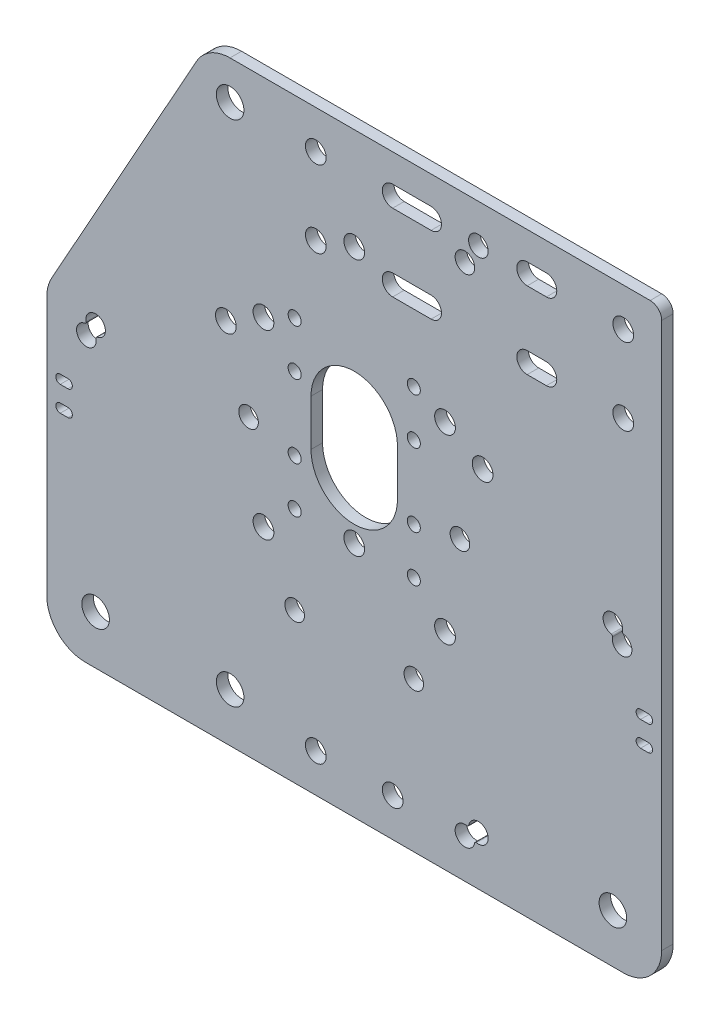
SolidWorks part; units mm, degrees
ref_plane "Ebene vorne" through (0, 0, 0) normal (0, 0, 1) x (1, 0, 0)
ref_plane "Ebene oben" through (0, 0, 0) normal (0, 1, 0) x (1, 0, 0)
ref_plane "Ebene rechts" through (0, 0, 0) normal (1, 0, 0) x (0, 0, -1)
sketch "Model" plane through (0, 0, 0) normal (0, 0, 1) x (1, 0, 0)
  line L0 (157, 155) -> (47.6787, 155)
  line L1 (38.941, 149.8633) -> (1.2623, 82.1679)
  line L2 (0, 77.3045) -> (0, 10)
  line L3 (10, 0) -> (150, 0)
  line L4 (160, 10) -> (160, 152)
  line L5 (68.75, 89.3) -> (68.75, 77.3)
  line L6 (91.25, 77.3) -> (91.25, 89.3)
  line L7 (130, 147.7) -> (125, 147.7)
  line L8 (125, 142.3) -> (130, 142.3)
  line L9 (130, 127.7) -> (125, 127.7)
  line L10 (125, 122.3) -> (130, 122.3)
  line L11 (100, 127.7) -> (90, 127.7)
  line L12 (90, 122.3) -> (100, 122.3)
  line L13 (100, 147.7) -> (90, 147.7)
  line L14 (90, 142.3) -> (100, 142.3)
  line L15 (5.5, 55.15) -> (3.5, 55.15)
  line L16 (3.5, 52.85) -> (5.5, 52.85)
  line L17 (5.5, 61.65) -> (3.5, 61.65)
  line L18 (3.5, 59.35) -> (5.5, 59.35)
  line L19 (156.5, 55.15) -> (154.5, 55.15)
  line L20 (154.5, 52.85) -> (156.5, 52.85)
  line L21 (156.5, 61.65) -> (154.5, 61.65)
  line L22 (154.5, 59.35) -> (156.5, 59.35)
  circle A0 centre (12.7, 12.7) radius 3.59
  circle A1 centre (47.7, 12.7) radius 3.59
  circle A2 centre (147.3, 12.7) radius 3.59
  circle A3 centre (47.7, 145) radius 3.59
  circle A4 centre (112.3, 145) radius 2.55
  circle A5 centre (52.5, 76.5) radius 2.55
  circle A6 centre (107.5, 76.5) radius 2.55
  circle A7 centre (64.5, 39) radius 2.55
  circle A8 centre (95.5, 39) radius 2.55
  circle A9 centre (64.5, 61.8) radius 1.7
  circle A10 centre (64.5, 73.8) radius 1.7
  circle A11 centre (64.5, 92.8) radius 1.7
  circle A12 centre (64.5, 104.8) radius 1.7
  circle A13 centre (95.5, 61.8) radius 1.7
  circle A14 centre (95.5, 73.8) radius 1.7
  circle A15 centre (95.5, 92.8) radius 1.7
  circle A16 centre (95.5, 104.8) radius 1.7
  circle A17 centre (56.38, 53.68) radius 2.7
  circle A18 centre (103.62, 53.68) radius 2.7
  circle A19 centre (103.62, 100.92) radius 2.7
  circle A20 centre (56.38, 100.92) radius 2.7
  circle A21 centre (70, 145) radius 2.7
  circle A22 centre (150, 145) radius 2.7
  circle A23 centre (150, 125) radius 2.7
  circle A24 centre (108.8, 139.5) radius 2.55
  circle A25 centre (80, 61.8) radius 2.7
  circle A26 centre (113.4037, 95.2037) radius 2.7
  circle A27 centre (80, 128.6074) radius 2.7
  circle A28 centre (46.5963, 95.2037) radius 2.7
  circle A29 centre (90, 10) radius 2.7
  circle A30 centre (70, 10) radius 2.7
  circle A31 centre (70, 125) radius 2.7
  arc A32 (47.6787, 155) -> (38.941, 149.8633) centre (47.6787, 145) ccw
  arc A33 (1.2623, 82.1679) -> (0, 77.3045) centre (10, 77.3045) ccw
  arc A34 (0, 10) -> (10, 0) centre (10, 10) ccw
  arc A35 (150, 0) -> (160, 10) centre (150, 10) ccw
  arc A36 (160, 152) -> (157, 155) centre (157, 152) ccw
  arc A37 (109.3109, 12.7983) -> (111.3145, 9.8763) centre (108.8, 10.3) ccw
  arc A38 (111.7891, 10.2017) -> (111.3145, 9.8763) centre (111.709, 9.8098) ccw
  arc A39 (111.7891, 10.2017) -> (109.7855, 13.1237) centre (112.3, 12.7) ccw
  arc A40 (109.3109, 12.7983) -> (109.7855, 13.1237) centre (109.391, 13.1902) ccw
  arc A41 (147.2017, 74.3109) -> (150.1237, 76.3145) centre (149.7, 73.8) ccw
  arc A42 (149.7983, 76.7891) -> (150.1237, 76.3145) centre (150.1902, 76.709) ccw
  arc A43 (149.7983, 76.7891) -> (146.8763, 74.7855) centre (147.3, 77.3) ccw
  arc A44 (147.2017, 74.3109) -> (146.8763, 74.7855) centre (146.8098, 74.391) ccw
  arc A45 (91.25, 89.3) -> (68.75, 89.3) centre (80, 89.3) ccw
  arc A46 (68.75, 77.3) -> (91.25, 77.3) centre (80, 77.3) ccw
  arc A47 (130, 142.3) -> (130, 147.7) centre (130, 145) ccw
  arc A48 (125, 147.7) -> (125, 142.3) centre (125, 145) ccw
  arc A49 (130, 122.3) -> (130, 127.7) centre (130, 125) ccw
  arc A50 (125, 127.7) -> (125, 122.3) centre (125, 125) ccw
  arc A51 (100, 122.3) -> (100, 127.7) centre (100, 125) ccw
  arc A52 (90, 127.7) -> (90, 122.3) centre (90, 125) ccw
  arc A53 (100, 142.3) -> (100, 147.7) centre (100, 145) ccw
  arc A54 (90, 147.7) -> (90, 142.3) centre (90, 145) ccw
  arc A55 (5.5, 52.85) -> (5.5, 55.15) centre (5.5, 54) ccw
  arc A56 (3.5, 55.15) -> (3.5, 52.85) centre (3.5, 54) ccw
  arc A57 (5.5, 59.35) -> (5.5, 61.65) centre (5.5, 60.5) ccw
  arc A58 (3.5, 61.65) -> (3.5, 59.35) centre (3.5, 60.5) ccw
  arc A59 (156.5, 52.85) -> (156.5, 55.15) centre (156.5, 54) ccw
  arc A60 (154.5, 55.15) -> (154.5, 52.85) centre (154.5, 54) ccw
  arc A61 (156.5, 59.35) -> (156.5, 61.65) centre (156.5, 60.5) ccw
  arc A62 (154.5, 61.65) -> (154.5, 59.35) centre (154.5, 60.5) ccw
  arc A63 (13.1237, 74.7855) -> (10.2017, 76.7891) centre (12.7, 77.3) ccw
  arc A64 (9.8763, 76.3145) -> (10.2017, 76.7891) centre (9.8098, 76.709) ccw
  arc A65 (9.8763, 76.3145) -> (12.7983, 74.3109) centre (10.3, 73.8) ccw
  arc A66 (13.1237, 74.7855) -> (12.7983, 74.3109) centre (13.1902, 74.391) ccw
extrude "Aufsatz-Linear austragen1" add sketch "Model" along normal blind 3
